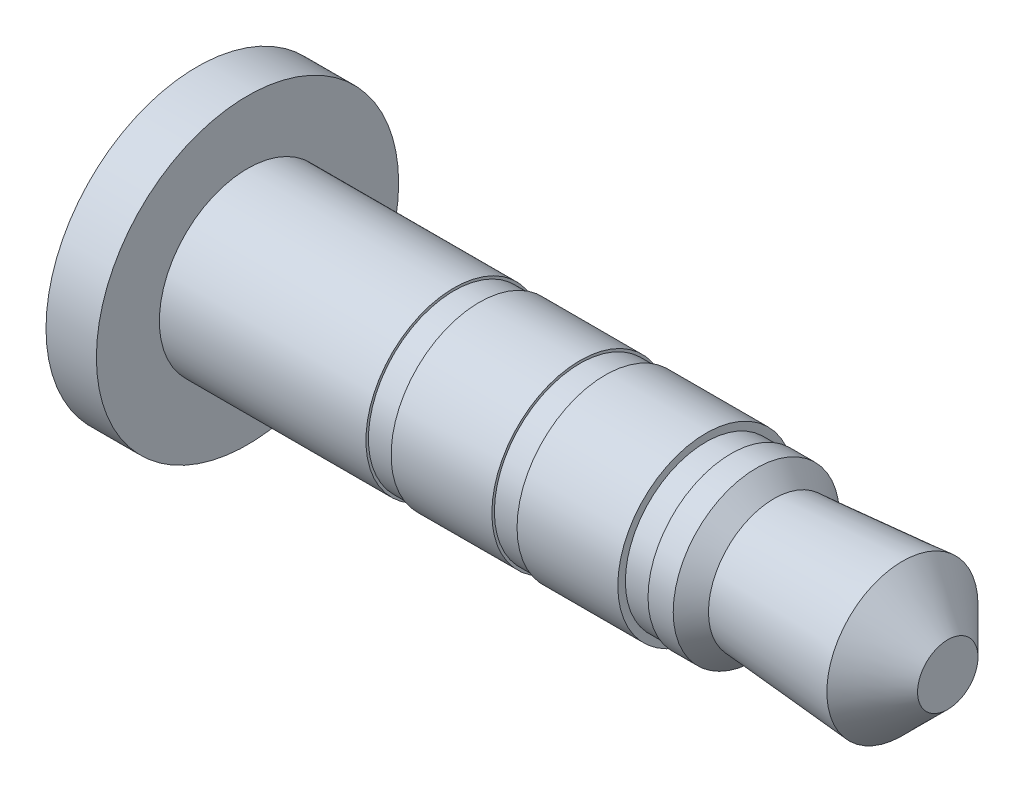
SolidWorks part; units mm, degrees
ref_plane "Plan de face" through (0, 0, 0) normal (0, 0, 1) x (1, 0, 0)
ref_plane "Plan de dessus" through (0, 0, 0) normal (0, 1, 0) x (1, 0, 0)
ref_plane "Plan de droite" through (0, 0, 0) normal (1, 0, 0) x (0, 0, -1)
sketch "Esquisse1" plane through (0, 0, 0) normal (0, 0, 1) x (1, 0, 0)
  line L0 (0, 0) -> (0, 1.75) construction
  line L1 (0, 1.75) -> (10, 1.75)
  line L2 (10, 1.75) -> (10.45, 1.3)
  line L3 (10.45, 1.3) -> (13, 1.5)
  line L4 (13, 1.5) -> (13.9, 0.6)
  line L5 (13.9, 0.6) -> (13.9, 0)
  line L6 (13.9, 0) -> (0, 0)
  line L7 (0, 1.75) -> (0, 3)
  line L8 (0, 3) -> (-1, 3)
  line L9 (-1, 3) -> (-1, 0)
  line L10 (-1, 0) -> (0, 0)
  dimension "D1" = 45
  dimension "D2" = 1.75
  dimension "D3" = 0.6
  dimension "D4" = 1.5
  dimension "D5" = 1.3
  dimension "D6" = 1
  dimension "D7" = 3
  dimension "D8" = 11
  dimension "D9" = 14
  dimension "D10" = 45
revolve "Révolution1" add sketch "Esquisse1" angle 360 about L6
sketch "Esquisse2" plane through (0, 0, 0) normal (0, 0, 1) x (1, 0, 0)
  line L0 (0, 0) -> (13.9, 0) construction
  line L1 (13.9, -0.6) -> (13.9, 0.6) construction
  line L2 (10, 1.75) -> (0, 1.75) construction
  line L3 (9.1, 1.75) -> (10.1, 1.75)
  line L4 (9.1, 1.75) -> (9.1, 1.65)
  line L5 (9.1, 1.65) -> (10.1, 1.65)
  line L6 (10.1, 1.75) -> (10.1, 1.65)
  line L8 (10.45, 1.3) -> (10, 1.75) construction
  dimension "D1" = 1
  dimension "D2" = 0.1
revolve "End of connector" cut sketch "Esquisse2" angle 360 about L0
sketch "Esquisse3" plane through (0, 0, 0) normal (0, 0, 1) x (1, 0, 0)
  line L1 (9.1, 1.65) -> (9.6, 1.65)
  line L2 (9.1, 1.65) -> (9.1, 1.6)
  line L3 (9.1, 1.6) -> (9.6, 1.6)
  line L4 (9.6, 1.65) -> (9.6, 1.6)
  dimension "D1" = 0.5
  dimension "D2" = 0.05
revolve "First connector separation" cut sketch "Esquisse3" angle 360 about axis through (13.9, 0, 0) along (1, 0, 0)
sketch "Esquisse4" plane through (0, 0, 0) normal (0, 0, 1) x (1, 0, 0)
  line L0 (9.1, 1.75) -> (0, 1.75) construction
  line L1 (7.1, 1.75) -> (6.6, 1.75)
  line L2 (7.1, 1.75) -> (7.1, 1.7)
  line L3 (7.1, 1.7) -> (6.6, 1.7)
  line L4 (6.6, 1.75) -> (6.6, 1.7)
  line L5 (9.1, -1.75) -> (9.1, 1.75) construction
  dimension "D1" = 0.5
  dimension "D2" = 0.05
  dimension "D3" = 2
revolve "Second connector separation" cut sketch "Esquisse4" angle 360 about axis through (13.9, 0, 0) along (1, 0, 0)
sketch "Esquisse5" plane through (0, 0, 0) normal (0, 0, 1) x (1, 0, 0)
  line L0 (6.6, 1.75) -> (0, 1.75) construction
  line L1 (4.1, 1.75) -> (4.6, 1.75)
  line L2 (4.1, 1.75) -> (4.1, 1.7)
  line L3 (4.1, 1.7) -> (4.6, 1.7)
  line L4 (4.6, 1.75) -> (4.6, 1.7)
  line L5 (6.6, -1.75) -> (6.6, 1.75) construction
  dimension "D1" = 0.5
  dimension "D2" = 0.05
  dimension "D3" = 2
revolve "Third connector sepatation" cut sketch "Esquisse5" angle 360 about axis through (0, 0, 0) along (-1, 0, 0)
equation "\"D2@Esquisse5\"=\"D2@Esquisse4\""
equation "\"D1@Esquisse5\"=\"D1@Esquisse4\""
equation "\"D3@Esquisse5\"=\"D3@Esquisse4\""
equation "\"D1@Esquisse4\"=\"D1@Esquisse3\""
equation "\"D2@Esquisse4\"=\"D2@Esquisse3\""
